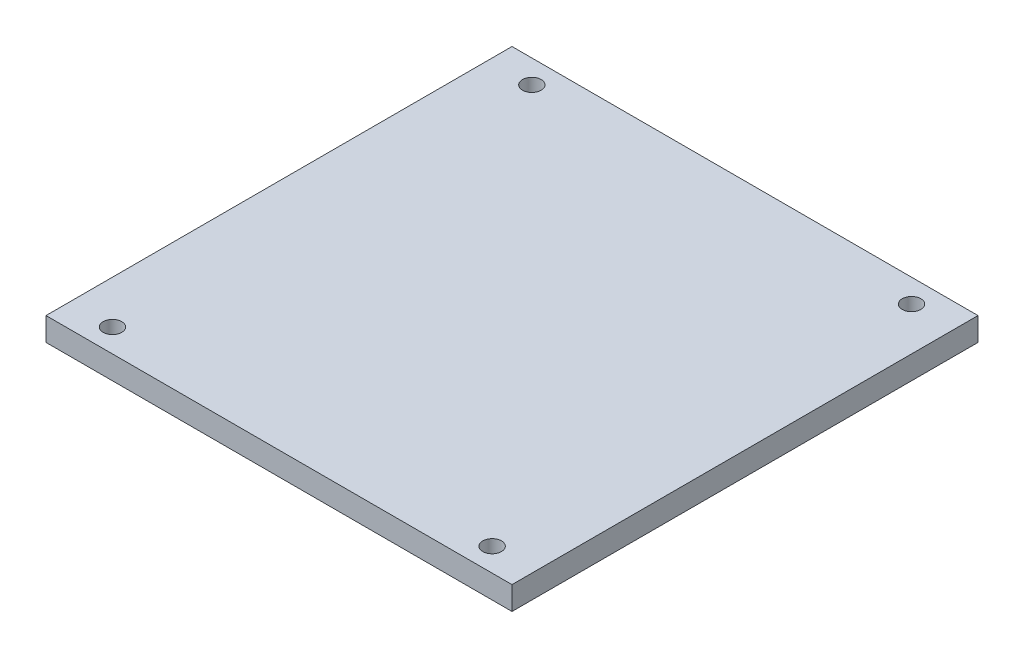
SolidWorks part; units mm, degrees
material "6061 Alloy"
ref_plane "Front" through (0, 0, 0) normal (0, 0, 1) x (1, 0, 0)
ref_plane "Top" through (0, 0, 0) normal (0, 1, 0) x (1, 0, 0)
ref_plane "Right" through (0, 0, 0) normal (1, 0, 0) x (0, 0, -1)
sketch "Sketch1" plane through (0, 0, 0) normal (0, 1, 0) x (1, 0, 0)
  line L1 (-63.5, -63.5) -> (63.5, -63.5)
  line L2 (-63.5, -63.5) -> (-63.5, 63.5)
  line L3 (-63.5, 63.5) -> (63.5, 63.5)
  line L4 (63.5, -63.5) -> (63.5, 63.5)
  line L5 (-63.5, -63.5) -> (63.5, 63.5) construction
  line L6 (-63.5, 63.5) -> (63.5, -63.5) construction
  point P0 (0, 0)
  dimension "D1" = 127
  dimension "D2" = 127
extrude "Boss-Extrude1" add sketch "Sketch1" along normal blind 6.35
sketch "Sketch3" plane through (0, 6.35, 0) normal (0, 1, 0) x (1, 0, 0)
  circle A0 centre (-51.7381, 57.15) radius 2.54
  circle A1 centre (51.7381, 57.15) radius 2.54
  circle A2 centre (-51.7381, -57.15) radius 2.54
  circle A3 centre (51.7381, -57.15) radius 2.54
  point P8 (-63.5, 63.5)
extrude "Cut-Extrude2" cut sketch "Sketch3" against normal blind 9.525
